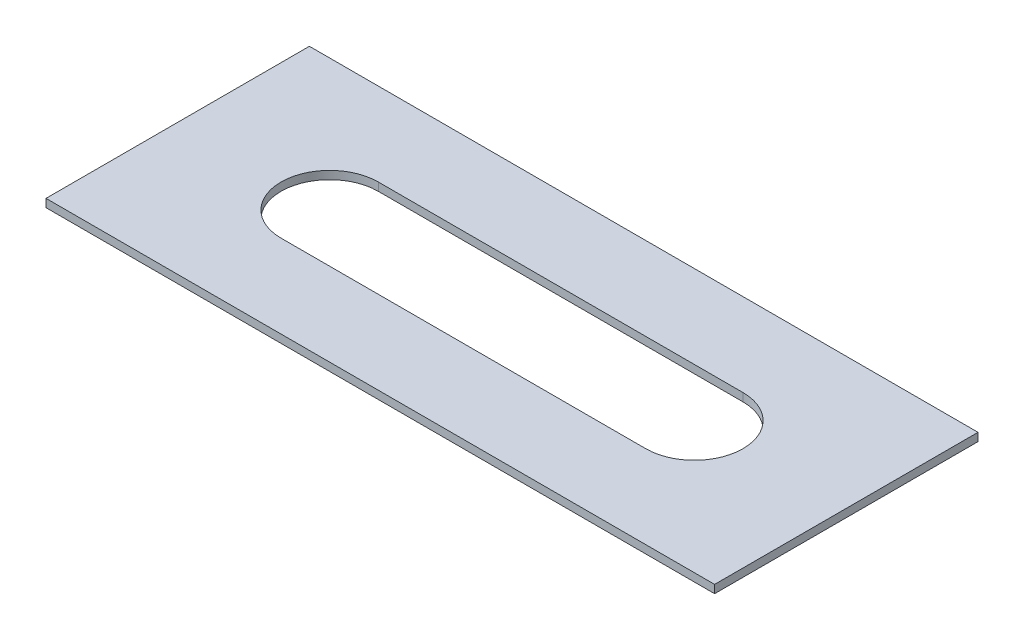
SolidWorks part; units mm, degrees
ref_plane "Alzado" through (0, 0, 0) normal (0, 0, 1) x (1, 0, 0)
ref_plane "Planta" through (0, 0, 0) normal (0, 1, 0) x (1, 0, 0)
ref_plane "Vista lateral" through (0, 0, 0) normal (1, 0, 0) x (0, 0, -1)
sketch "Croquis1" plane through (0, 0, 0) normal (0, 1, 0) x (1, 0, 0)
  line L1 (0, 0) -> (165, 0)
  line L2 (0, 0) -> (0, 65)
  line L3 (0, 65) -> (165, 65)
  line L4 (165, 0) -> (165, 65)
  line L6 (37.5, 32.5) -> (127.5, 32.5) construction
  line L7 (37.5, 44.5) -> (127.5, 44.5)
  line L8 (37.5, 20.5) -> (127.5, 20.5)
  arc A0 (37.5, 44.5) -> (37.5, 20.5) centre (37.5, 32.5) ccw
  arc A1 (127.5, 20.5) -> (127.5, 44.5) centre (127.5, 32.5) ccw
  point P7 (82.5, 32.5)
extrude "Saliente-Extruir1" add sketch "Croquis1" along normal blind 2
